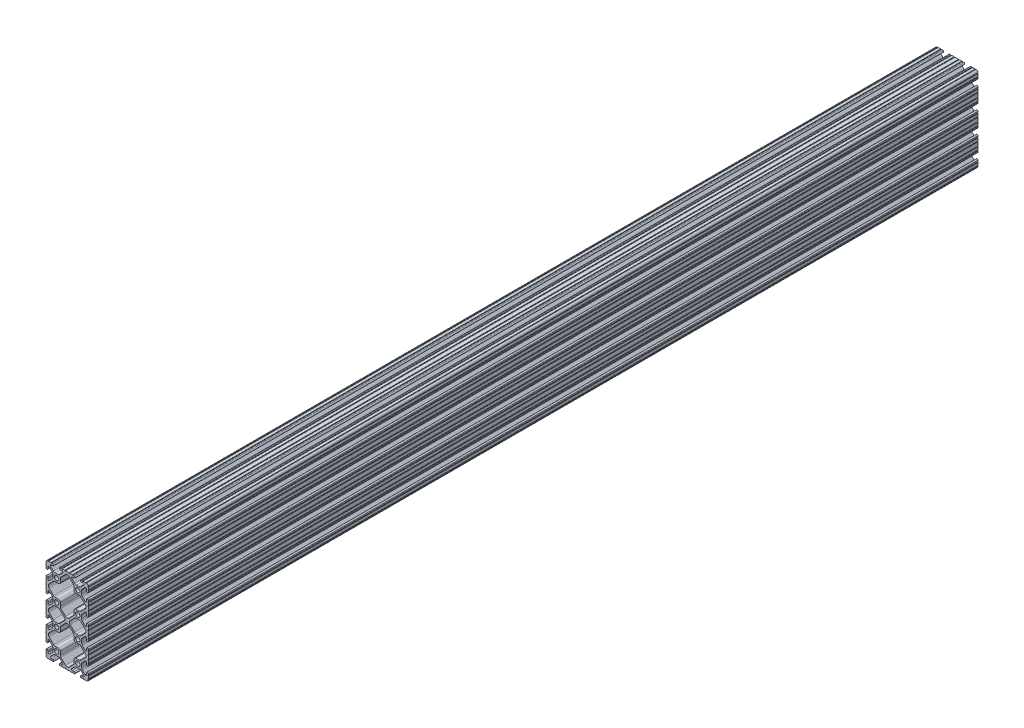
SolidWorks part; units mm, degrees
ref_plane "Front Plane" through (0, 0, 0) normal (0, 0, 1) x (1, 0, 0)
ref_plane "Top Plane" through (0, 0, 0) normal (0, 1, 0) x (1, 0, 0)
ref_plane "Right Plane" through (0, 0, 0) normal (1, 0, 0) x (0, 0, -1)
sketch "Sketch1" plane through (0, 0, 0) normal (0, 0, 1) x (1, 0, 0)
  line L0 (2.286, 55.2958) -> (-2.0184, 55.2958)
  line L1 (-3.5809, 55.943) -> (-9.0725, 61.4345)
  line L2 (-9.0725, 65.5655) -> (-3.5809, 71.057)
  line L3 (-2.0184, 71.7042) -> (2.286, 71.7042)
  line L4 (4.4958, 73.914) -> (4.4958, 78.2184)
  line L5 (5.143, 79.7809) -> (10.6345, 85.2725)
  line L6 (14.7655, 85.2725) -> (20.257, 79.7809)
  line L7 (20.9042, 78.2184) -> (20.9042, 73.914)
  line L8 (23.114, 71.7042) -> (27.4184, 71.7042)
  line L9 (28.9809, 71.057) -> (34.4725, 65.5655)
  line L10 (34.4725, 61.4345) -> (28.9809, 55.943)
  line L11 (27.4184, 55.2958) -> (23.114, 55.2958)
  line L12 (20.9042, 53.086) -> (20.9042, 48.7816)
  line L13 (20.257, 47.2191) -> (14.7655, 41.7275)
  line L14 (10.6345, 41.7275) -> (5.143, 47.2191)
  line L15 (4.4958, 48.7816) -> (4.4958, 53.086)
  line L16 (4.4958, 23.114) -> (4.4958, 27.4184)
  line L17 (5.143, 28.9809) -> (10.6345, 34.4725)
  line L18 (14.7655, 34.4725) -> (20.257, 28.9809)
  line L19 (20.9042, 27.4184) -> (20.9042, 23.114)
  line L20 (23.114, 20.9042) -> (27.4184, 20.9042)
  line L21 (28.9809, 20.257) -> (34.4725, 14.7655)
  line L22 (34.4725, 10.6345) -> (28.9809, 5.143)
  line L23 (27.4184, 4.4958) -> (23.114, 4.4958)
  line L24 (20.9042, 2.286) -> (20.9042, -2.0184)
  line L25 (20.257, -3.5809) -> (14.7655, -9.0725)
  line L26 (10.6345, -9.0725) -> (5.143, -3.5809)
  line L27 (4.4958, -2.0184) -> (4.4958, 2.286)
  line L28 (2.286, 4.4958) -> (-2.0184, 4.4958)
  line L29 (-3.5809, 5.143) -> (-9.0725, 10.6345)
  line L30 (-9.0725, 14.7655) -> (-3.5809, 20.257)
  line L31 (-2.0184, 20.9042) -> (2.286, 20.9042)
  line L32 (27.0186, 29.8958) -> (23.7824, 29.8958)
  line L33 (21.5373, 30.8258) -> (16.3286, 36.0346)
  line L34 (16.3286, 40.1654) -> (21.5373, 45.3742)
  line L35 (23.7824, 46.3042) -> (27.0186, 46.3042)
  line L36 (29.2636, 45.3743) -> (34.4725, 40.1655)
  line L37 (34.4725, 36.0345) -> (29.2636, 30.8257)
  line L38 (1.6176, 29.8958) -> (-1.6186, 29.8958)
  line L39 (-3.8636, 30.8257) -> (-9.0725, 36.0345)
  line L40 (-9.0725, 40.1655) -> (-3.8636, 45.3743)
  line L41 (-1.6186, 46.3042) -> (1.6176, 46.3042)
  line L42 (3.8627, 45.3742) -> (9.0714, 40.1654)
  line L43 (9.0714, 36.0346) -> (3.8627, 30.8258)
  line L44 (-12.7, 40.2336) -> (-12.7, 35.9664)
  line L45 (-12.7, 34.9504) -> (-12.7, 32.004)
  line L46 (-12.7, 30.988) -> (-12.7, 29.7434)
  line L47 (-10.4902, 29.7434) -> (-10.4902, 31.8743)
  line L48 (-8.7558, 32.5927) -> (-5.4258, 29.2627)
  line L49 (-4.4958, 27.0176) -> (-4.4958, 23.7824)
  line L50 (-5.4258, 21.5373) -> (-8.7558, 18.2073)
  line L51 (-10.4902, 18.9257) -> (-10.4902, 21.0566)
  line L52 (-12.7, 21.0566) -> (-12.7, 19.812)
  line L53 (-12.7, 18.796) -> (-12.7, 15.8496)
  line L54 (-12.7, 14.8336) -> (-12.7, 10.5664)
  line L55 (-12.7, 9.5504) -> (-12.7, 6.604)
  line L56 (-12.7, 5.588) -> (-12.7, 4.3434)
  line L57 (-10.4902, 4.3434) -> (-10.4902, 6.4743)
  line L58 (-8.7558, 7.1927) -> (-5.4258, 3.8627)
  line L59 (-4.4958, 1.6176) -> (-4.4958, -1.6176)
  line L60 (-5.4258, -3.8627) -> (-8.7558, -7.1927)
  line L61 (-10.4902, -6.4743) -> (-10.4902, -4.3434)
  line L62 (-12.7, -4.3434) -> (-12.7, -5.588)
  line L63 (-12.7, -6.604) -> (-12.7, -9.5504)
  line L64 (-9.5504, -12.7) -> (-6.604, -12.7)
  line L65 (-5.588, -12.7) -> (-4.3434, -12.7)
  line L66 (-4.3434, -10.4902) -> (-6.4743, -10.4902)
  line L67 (-7.1927, -8.7558) -> (-3.8627, -5.4258)
  line L68 (-1.6176, -4.4958) -> (1.6176, -4.4958)
  line L69 (3.8627, -5.4258) -> (7.1927, -8.7558)
  line L70 (6.4743, -10.4902) -> (4.3434, -10.4902)
  line L71 (4.3434, -12.7) -> (5.588, -12.7)
  line L72 (6.604, -12.7) -> (9.5504, -12.7)
  line L73 (10.5664, -12.7) -> (14.8336, -12.7)
  line L74 (15.8496, -12.7) -> (18.796, -12.7)
  line L75 (19.812, -12.7) -> (21.0566, -12.7)
  line L76 (21.0566, -10.4902) -> (18.9257, -10.4902)
  line L77 (18.2073, -8.7558) -> (21.5373, -5.4258)
  line L78 (23.7824, -4.4958) -> (27.0176, -4.4958)
  line L79 (29.2627, -5.4258) -> (32.5927, -8.7558)
  line L80 (31.8743, -10.4902) -> (29.7434, -10.4902)
  line L81 (29.7434, -12.7) -> (30.988, -12.7)
  line L82 (32.004, -12.7) -> (34.9504, -12.7)
  line L83 (38.1, -9.5504) -> (38.1, -6.604)
  line L84 (38.1, -5.588) -> (38.1, -4.3434)
  line L85 (35.8902, -4.3434) -> (35.8902, -6.4743)
  line L86 (34.1558, -7.1927) -> (30.8258, -3.8627)
  line L87 (29.8958, -1.6176) -> (29.8958, 1.6176)
  line L88 (30.8258, 3.8627) -> (34.1558, 7.1927)
  line L89 (35.8902, 6.4743) -> (35.8902, 4.3434)
  line L90 (38.1, 4.3434) -> (38.1, 5.588)
  line L91 (38.1, 6.604) -> (38.1, 9.5504)
  line L92 (38.1, 10.5664) -> (38.1, 14.8336)
  line L93 (38.1, 15.8496) -> (38.1, 18.796)
  line L94 (38.1, 19.812) -> (38.1, 21.0566)
  line L95 (35.8902, 21.0566) -> (35.8902, 18.9257)
  line L96 (34.1558, 18.2073) -> (30.8258, 21.5373)
  line L97 (29.8958, 23.7824) -> (29.8958, 27.0176)
  line L98 (30.8258, 29.2627) -> (34.1558, 32.5927)
  line L99 (35.8902, 31.8743) -> (35.8902, 29.7434)
  line L100 (38.1, 29.7434) -> (38.1, 30.988)
  line L101 (38.1, 32.004) -> (38.1, 34.9504)
  line L102 (38.1, 35.9664) -> (38.1, 40.2336)
  line L103 (38.1, 41.2496) -> (38.1, 44.196)
  line L104 (38.1, 45.212) -> (38.1, 46.4566)
  line L105 (35.8902, 46.4566) -> (35.8902, 44.3257)
  line L106 (34.1558, 43.6073) -> (30.8258, 46.9373)
  line L107 (29.8958, 49.1824) -> (29.8958, 52.4176)
  line L108 (30.8258, 54.6627) -> (34.1558, 57.9927)
  line L109 (35.8902, 57.2743) -> (35.8902, 55.1434)
  line L110 (38.1, 55.1434) -> (38.1, 56.388)
  line L111 (38.1, 57.404) -> (38.1, 60.3504)
  line L112 (38.1, 61.3664) -> (38.1, 65.6336)
  line L113 (38.1, 66.6496) -> (38.1, 69.596)
  line L114 (38.1, 70.612) -> (38.1, 71.8566)
  line L115 (35.8902, 71.8566) -> (35.8902, 69.7257)
  line L116 (34.1558, 69.0073) -> (30.8258, 72.3373)
  line L117 (29.8958, 74.5824) -> (29.8958, 77.8176)
  line L118 (30.8258, 80.0627) -> (34.1558, 83.3927)
  line L119 (35.8902, 82.6743) -> (35.8902, 80.5434)
  line L120 (38.1, 80.5434) -> (38.1, 81.788)
  line L121 (38.1, 82.804) -> (38.1, 85.7504)
  line L122 (34.9504, 88.9) -> (32.004, 88.9)
  line L123 (30.988, 88.9) -> (29.7434, 88.9)
  line L124 (29.7434, 86.6902) -> (31.8743, 86.6902)
  line L125 (32.5927, 84.9558) -> (29.2627, 81.6258)
  line L126 (27.0176, 80.6958) -> (23.7824, 80.6958)
  line L127 (21.5373, 81.6258) -> (18.2073, 84.9558)
  line L128 (18.9257, 86.6902) -> (21.0566, 86.6902)
  line L129 (21.0566, 88.9) -> (19.812, 88.9)
  line L130 (18.796, 88.9) -> (15.8496, 88.9)
  line L131 (14.8336, 88.9) -> (10.5664, 88.9)
  line L132 (9.5504, 88.9) -> (6.604, 88.9)
  line L133 (5.588, 88.9) -> (4.3434, 88.9)
  line L134 (4.3434, 86.6902) -> (6.4743, 86.6902)
  line L135 (7.1927, 84.9558) -> (3.8627, 81.6258)
  line L136 (1.6176, 80.6958) -> (-1.6176, 80.6958)
  line L137 (-3.8627, 81.6258) -> (-7.1927, 84.9558)
  line L138 (-6.4743, 86.6902) -> (-4.3434, 86.6902)
  line L139 (-4.3434, 88.9) -> (-5.588, 88.9)
  line L140 (-6.604, 88.9) -> (-9.5504, 88.9)
  line L141 (-12.7, 85.7504) -> (-12.7, 82.804)
  line L142 (-12.7, 81.788) -> (-12.7, 80.5434)
  line L143 (-10.4902, 80.5434) -> (-10.4902, 82.6743)
  line L144 (-8.7558, 83.3927) -> (-5.4258, 80.0627)
  line L145 (-4.4958, 77.8176) -> (-4.4958, 74.5824)
  line L146 (-5.4258, 72.3373) -> (-8.7558, 69.0073)
  line L147 (-10.4902, 69.7257) -> (-10.4902, 71.8566)
  line L148 (-12.7, 71.8566) -> (-12.7, 70.612)
  line L149 (-12.7, 69.596) -> (-12.7, 66.6496)
  line L150 (-12.7, 65.6336) -> (-12.7, 61.3664)
  line L151 (-12.7, 60.3504) -> (-12.7, 57.404)
  line L152 (-12.7, 56.388) -> (-12.7, 55.1434)
  line L153 (-10.4902, 55.1434) -> (-10.4902, 57.2743)
  line L154 (-8.7558, 57.9927) -> (-5.4258, 54.6627)
  line L155 (-4.4958, 52.4176) -> (-4.4958, 49.1824)
  line L156 (-5.4258, 46.9373) -> (-8.7558, 43.6073)
  line L157 (-10.4902, 44.3257) -> (-10.4902, 46.4566)
  line L158 (-12.7, 46.4566) -> (-12.7, 45.212)
  line L159 (-12.7, 44.196) -> (-12.7, 41.2496)
  arc A0 (4.4958, 53.086) -> (2.286, 55.2958) centre (2.286, 53.086) ccw
  arc A1 (-3.5809, 55.943) -> (-2.0184, 55.2958) centre (-2.0184, 57.5056) ccw
  arc A2 (-9.0725, 65.5655) -> (-9.0725, 61.4345) centre (-7.0071, 63.5) ccw
  arc A3 (-2.0184, 71.7042) -> (-3.5809, 71.057) centre (-2.0184, 69.4944) ccw
  arc A4 (2.286, 71.7042) -> (4.4958, 73.914) centre (2.286, 73.914) ccw
  arc A5 (5.143, 79.7809) -> (4.4958, 78.2184) centre (6.7056, 78.2184) ccw
  arc A6 (14.7655, 85.2725) -> (10.6345, 85.2725) centre (12.7, 83.2071) ccw
  arc A7 (20.9042, 78.2184) -> (20.257, 79.7809) centre (18.6944, 78.2184) ccw
  arc A8 (20.9042, 73.914) -> (23.114, 71.7042) centre (23.114, 73.914) ccw
  arc A9 (28.9809, 71.057) -> (27.4184, 71.7042) centre (27.4184, 69.4944) ccw
  arc A10 (34.4725, 61.4345) -> (34.4725, 65.5655) centre (32.4071, 63.5) ccw
  arc A11 (27.4184, 55.2958) -> (28.9809, 55.943) centre (27.4184, 57.5056) ccw
  arc A12 (23.114, 55.2958) -> (20.9042, 53.086) centre (23.114, 53.086) ccw
  arc A13 (20.257, 47.2191) -> (20.9042, 48.7816) centre (18.6944, 48.7816) ccw
  arc A14 (10.6345, 41.7275) -> (14.7655, 41.7275) centre (12.7, 43.7929) ccw
  arc A15 (4.4958, 48.7816) -> (5.143, 47.2191) centre (6.7056, 48.7816) ccw
  arc A16 (2.286, 20.9042) -> (4.4958, 23.114) centre (2.286, 23.114) ccw
  arc A17 (5.143, 28.9809) -> (4.4958, 27.4184) centre (6.7056, 27.4184) ccw
  arc A18 (14.7655, 34.4725) -> (10.6345, 34.4725) centre (12.7, 32.4071) ccw
  arc A19 (20.9042, 27.4184) -> (20.257, 28.9809) centre (18.6944, 27.4184) ccw
  arc A20 (20.9042, 23.114) -> (23.114, 20.9042) centre (23.114, 23.114) ccw
  arc A21 (28.9809, 20.257) -> (27.4184, 20.9042) centre (27.4184, 18.6944) ccw
  arc A22 (34.4725, 10.6345) -> (34.4725, 14.7655) centre (32.4071, 12.7) ccw
  arc A23 (27.4184, 4.4958) -> (28.9809, 5.143) centre (27.4184, 6.7056) ccw
  arc A24 (23.114, 4.4958) -> (20.9042, 2.286) centre (23.114, 2.286) ccw
  arc A25 (20.257, -3.5809) -> (20.9042, -2.0184) centre (18.6944, -2.0184) ccw
  arc A26 (10.6345, -9.0725) -> (14.7655, -9.0725) centre (12.7, -7.0071) ccw
  arc A27 (4.4958, -2.0184) -> (5.143, -3.5809) centre (6.7056, -2.0184) ccw
  arc A28 (4.4958, 2.286) -> (2.286, 4.4958) centre (2.286, 2.286) ccw
  arc A29 (-3.5809, 5.143) -> (-2.0184, 4.4958) centre (-2.0184, 6.7056) ccw
  arc A30 (-9.0725, 14.7655) -> (-9.0725, 10.6345) centre (-7.0071, 12.7) ccw
  arc A31 (-2.0184, 20.9042) -> (-3.5809, 20.257) centre (-2.0184, 18.6944) ccw
  arc A32 (27.0186, 29.8958) -> (29.2636, 30.8257) centre (27.0186, 33.0708) ccw
  arc A33 (21.5373, 30.8258) -> (23.7824, 29.8958) centre (23.7824, 33.0708) ccw
  arc A34 (16.3286, 40.1654) -> (16.3286, 36.0346) centre (18.3941, 38.1) ccw
  arc A35 (23.7824, 46.3042) -> (21.5373, 45.3742) centre (23.7824, 43.1292) ccw
  arc A36 (29.2636, 45.3743) -> (27.0186, 46.3042) centre (27.0186, 43.1292) ccw
  arc A37 (34.4725, 36.0345) -> (34.4725, 40.1655) centre (32.4071, 38.1) ccw
  arc A38 (1.6176, 29.8958) -> (3.8627, 30.8258) centre (1.6176, 33.0708) ccw
  arc A39 (-3.8636, 30.8257) -> (-1.6186, 29.8958) centre (-1.6186, 33.0708) ccw
  arc A40 (-9.0725, 40.1655) -> (-9.0725, 36.0345) centre (-7.0071, 38.1) ccw
  arc A41 (-1.6186, 46.3042) -> (-3.8636, 45.3743) centre (-1.6186, 43.1292) ccw
  arc A42 (3.8627, 45.3742) -> (1.6176, 46.3042) centre (1.6176, 43.1292) ccw
  arc A43 (9.0714, 36.0346) -> (9.0714, 40.1654) centre (7.0059, 38.1) ccw
  circle A44 centre (25.4, 76.2) radius 2.6035
  circle A45 centre (0, 76.2) radius 2.6035
  circle A46 centre (25.4, 50.8) radius 2.6035
  circle A47 centre (0, 50.8) radius 2.6035
  circle A48 centre (25.4, 0) radius 2.6035
  circle A49 centre (0, 0) radius 2.6035
  circle A50 centre (25.4, 25.4) radius 2.6035
  circle A51 centre (0, 25.4) radius 2.6035
  arc A52 (-12.7, 34.9504) -> (-12.7, 35.9664) centre (-12.7, 35.4584) ccw
  arc A53 (-12.7, 30.988) -> (-12.7, 32.004) centre (-12.7, 31.496) ccw
  arc A54 (-12.7, 29.7434) -> (-10.4902, 29.7434) centre (-11.5951, 29.7434) ccw
  arc A55 (-8.7558, 32.5927) -> (-10.4902, 31.8743) centre (-9.4742, 31.8743) ccw
  arc A56 (-4.4958, 27.0176) -> (-5.4258, 29.2627) centre (-7.6708, 27.0176) ccw
  arc A57 (-5.4258, 21.5373) -> (-4.4958, 23.7824) centre (-7.6708, 23.7824) ccw
  arc A58 (-10.4902, 18.9257) -> (-8.7558, 18.2073) centre (-9.4742, 18.9257) ccw
  arc A59 (-10.4902, 21.0566) -> (-12.7, 21.0566) centre (-11.5951, 21.0566) ccw
  arc A60 (-12.7, 18.796) -> (-12.7, 19.812) centre (-12.7, 19.304) ccw
  arc A61 (-12.7, 14.8336) -> (-12.7, 15.8496) centre (-12.7, 15.3416) ccw
  arc A62 (-12.7, 9.5504) -> (-12.7, 10.5664) centre (-12.7, 10.0584) ccw
  arc A63 (-12.7, 5.588) -> (-12.7, 6.604) centre (-12.7, 6.096) ccw
  arc A64 (-12.7, 4.3434) -> (-10.4902, 4.3434) centre (-11.5951, 4.3434) ccw
  arc A65 (-8.7558, 7.1927) -> (-10.4902, 6.4743) centre (-9.4742, 6.4743) ccw
  arc A66 (-4.4958, 1.6176) -> (-5.4258, 3.8627) centre (-7.6708, 1.6176) ccw
  arc A67 (-5.4258, -3.8627) -> (-4.4958, -1.6176) centre (-7.6708, -1.6176) ccw
  arc A68 (-10.4902, -6.4743) -> (-8.7558, -7.1927) centre (-9.4742, -6.4743) ccw
  arc A69 (-10.4902, -4.3434) -> (-12.7, -4.3434) centre (-11.5951, -4.3434) ccw
  arc A70 (-12.7, -6.604) -> (-12.7, -5.588) centre (-12.7, -6.096) ccw
  arc A71 (-12.6998, -10.5664) -> (-12.7, -9.5504) centre (-12.7, -10.0584) ccw
  arc A72 (-12.6998, -10.5664) -> (-10.5664, -12.6998) centre (-10.5918, -10.5918) ccw
  arc A73 (-9.5504, -12.7) -> (-10.5664, -12.6998) centre (-10.0584, -12.7) ccw
  arc A74 (-5.588, -12.7) -> (-6.604, -12.7) centre (-6.096, -12.7) ccw
  arc A75 (-4.3434, -12.7) -> (-4.3434, -10.4902) centre (-4.3434, -11.5951) ccw
  arc A76 (-7.1927, -8.7558) -> (-6.4743, -10.4902) centre (-6.4743, -9.4742) ccw
  arc A77 (-1.6176, -4.4958) -> (-3.8627, -5.4258) centre (-1.6176, -7.6708) ccw
  arc A78 (3.8627, -5.4258) -> (1.6176, -4.4958) centre (1.6176, -7.6708) ccw
  arc A79 (6.4743, -10.4902) -> (7.1927, -8.7558) centre (6.4743, -9.4742) ccw
  arc A80 (4.3434, -10.4902) -> (4.3434, -12.7) centre (4.3434, -11.5951) ccw
  arc A81 (6.604, -12.7) -> (5.588, -12.7) centre (6.096, -12.7) ccw
  arc A82 (10.5664, -12.7) -> (9.5504, -12.7) centre (10.0584, -12.7) ccw
  arc A83 (15.8496, -12.7) -> (14.8336, -12.7) centre (15.3416, -12.7) ccw
  arc A84 (19.812, -12.7) -> (18.796, -12.7) centre (19.304, -12.7) ccw
  arc A85 (21.0566, -12.7) -> (21.0566, -10.4902) centre (21.0566, -11.5951) ccw
  arc A86 (18.2073, -8.7558) -> (18.9257, -10.4902) centre (18.9257, -9.4742) ccw
  arc A87 (23.7824, -4.4958) -> (21.5373, -5.4258) centre (23.7824, -7.6708) ccw
  arc A88 (29.2627, -5.4258) -> (27.0176, -4.4958) centre (27.0176, -7.6708) ccw
  arc A89 (31.8743, -10.4902) -> (32.5927, -8.7558) centre (31.8743, -9.4742) ccw
  arc A90 (29.7434, -10.4902) -> (29.7434, -12.7) centre (29.7434, -11.5951) ccw
  arc A91 (32.004, -12.7) -> (30.988, -12.7) centre (31.496, -12.7) ccw
  arc A92 (35.9664, -12.6998) -> (34.9504, -12.7) centre (35.4584, -12.7) ccw
  arc A93 (35.9664, -12.6998) -> (38.0998, -10.5664) centre (35.9918, -10.5918) ccw
  arc A94 (38.1, -9.5504) -> (38.0998, -10.5664) centre (38.1, -10.0584) ccw
  arc A95 (38.1, -5.588) -> (38.1, -6.604) centre (38.1, -6.096) ccw
  arc A96 (38.1, -4.3434) -> (35.8902, -4.3434) centre (36.9951, -4.3434) ccw
  arc A97 (34.1558, -7.1927) -> (35.8902, -6.4743) centre (34.8742, -6.4743) ccw
  arc A98 (29.8958, -1.6176) -> (30.8258, -3.8627) centre (33.0708, -1.6176) ccw
  arc A99 (30.8258, 3.8627) -> (29.8958, 1.6176) centre (33.0708, 1.6176) ccw
  arc A100 (35.8902, 6.4743) -> (34.1558, 7.1927) centre (34.8742, 6.4743) ccw
  arc A101 (35.8902, 4.3434) -> (38.1, 4.3434) centre (36.9951, 4.3434) ccw
  arc A102 (38.1, 6.604) -> (38.1, 5.588) centre (38.1, 6.096) ccw
  arc A103 (38.1, 10.5664) -> (38.1, 9.5504) centre (38.1, 10.0584) ccw
  arc A104 (38.1, 15.8496) -> (38.1, 14.8336) centre (38.1, 15.3416) ccw
  arc A105 (38.1, 19.812) -> (38.1, 18.796) centre (38.1, 19.304) ccw
  arc A106 (38.1, 21.0566) -> (35.8902, 21.0566) centre (36.9951, 21.0566) ccw
  arc A107 (34.1558, 18.2073) -> (35.8902, 18.9257) centre (34.8742, 18.9257) ccw
  arc A108 (29.8958, 23.7824) -> (30.8258, 21.5373) centre (33.0708, 23.7824) ccw
  arc A109 (30.8258, 29.2627) -> (29.8958, 27.0176) centre (33.0708, 27.0176) ccw
  arc A110 (35.8902, 31.8743) -> (34.1558, 32.5927) centre (34.8742, 31.8743) ccw
  arc A111 (35.8902, 29.7434) -> (38.1, 29.7434) centre (36.9951, 29.7434) ccw
  arc A112 (38.1, 32.004) -> (38.1, 30.988) centre (38.1, 31.496) ccw
  arc A113 (38.1, 35.9664) -> (38.1, 34.9504) centre (38.1, 35.4584) ccw
  arc A114 (38.1, 41.2496) -> (38.1, 40.2336) centre (38.1, 40.7416) ccw
  arc A115 (38.1, 45.212) -> (38.1, 44.196) centre (38.1, 44.704) ccw
  arc A116 (38.1, 46.4566) -> (35.8902, 46.4566) centre (36.9951, 46.4566) ccw
  arc A117 (34.1558, 43.6073) -> (35.8902, 44.3257) centre (34.8742, 44.3257) ccw
  arc A118 (29.8958, 49.1824) -> (30.8258, 46.9373) centre (33.0708, 49.1824) ccw
  arc A119 (30.8258, 54.6627) -> (29.8958, 52.4176) centre (33.0708, 52.4176) ccw
  arc A120 (35.8902, 57.2743) -> (34.1558, 57.9927) centre (34.8742, 57.2743) ccw
  arc A121 (35.8902, 55.1434) -> (38.1, 55.1434) centre (36.9951, 55.1434) ccw
  arc A122 (38.1, 57.404) -> (38.1, 56.388) centre (38.1, 56.896) ccw
  arc A123 (38.1, 61.3664) -> (38.1, 60.3504) centre (38.1, 60.8584) ccw
  arc A124 (38.1, 66.6496) -> (38.1, 65.6336) centre (38.1, 66.1416) ccw
  arc A125 (38.1, 70.612) -> (38.1, 69.596) centre (38.1, 70.104) ccw
  arc A126 (38.1, 71.8566) -> (35.8902, 71.8566) centre (36.9951, 71.8566) ccw
  arc A127 (34.1558, 69.0073) -> (35.8902, 69.7257) centre (34.8742, 69.7257) ccw
  arc A128 (29.8958, 74.5824) -> (30.8258, 72.3373) centre (33.0708, 74.5824) ccw
  arc A129 (30.8258, 80.0627) -> (29.8958, 77.8176) centre (33.0708, 77.8176) ccw
  arc A130 (35.8902, 82.6743) -> (34.1558, 83.3927) centre (34.8742, 82.6743) ccw
  arc A131 (35.8902, 80.5434) -> (38.1, 80.5434) centre (36.9951, 80.5434) ccw
  arc A132 (38.1, 82.804) -> (38.1, 81.788) centre (38.1, 82.296) ccw
  arc A133 (38.0998, 86.7664) -> (38.1, 85.7504) centre (38.1, 86.2584) ccw
  arc A134 (38.0998, 86.7664) -> (35.9664, 88.8998) centre (35.9918, 86.7918) ccw
  arc A135 (34.9504, 88.9) -> (35.9664, 88.8998) centre (35.4584, 88.9) ccw
  arc A136 (30.988, 88.9) -> (32.004, 88.9) centre (31.496, 88.9) ccw
  arc A137 (29.7434, 88.9) -> (29.7434, 86.6902) centre (29.7434, 87.7951) ccw
  arc A138 (32.5927, 84.9558) -> (31.8743, 86.6902) centre (31.8743, 85.6742) ccw
  arc A139 (27.0176, 80.6958) -> (29.2627, 81.6258) centre (27.0176, 83.8708) ccw
  arc A140 (21.5373, 81.6258) -> (23.7824, 80.6958) centre (23.7824, 83.8708) ccw
  arc A141 (18.9257, 86.6902) -> (18.2073, 84.9558) centre (18.9257, 85.6742) ccw
  arc A142 (21.0566, 86.6902) -> (21.0566, 88.9) centre (21.0566, 87.7951) ccw
  arc A143 (18.796, 88.9) -> (19.812, 88.9) centre (19.304, 88.9) ccw
  arc A144 (14.8336, 88.9) -> (15.8496, 88.9) centre (15.3416, 88.9) ccw
  arc A145 (9.5504, 88.9) -> (10.5664, 88.9) centre (10.0584, 88.9) ccw
  arc A146 (5.588, 88.9) -> (6.604, 88.9) centre (6.096, 88.9) ccw
  arc A147 (4.3434, 88.9) -> (4.3434, 86.6902) centre (4.3434, 87.7951) ccw
  arc A148 (7.1927, 84.9558) -> (6.4743, 86.6902) centre (6.4743, 85.6742) ccw
  arc A149 (1.6176, 80.6958) -> (3.8627, 81.6258) centre (1.6176, 83.8708) ccw
  arc A150 (-3.8627, 81.6258) -> (-1.6176, 80.6958) centre (-1.6176, 83.8708) ccw
  arc A151 (-6.4743, 86.6902) -> (-7.1927, 84.9558) centre (-6.4743, 85.6742) ccw
  arc A152 (-4.3434, 86.6902) -> (-4.3434, 88.9) centre (-4.3434, 87.7951) ccw
  arc A153 (-6.604, 88.9) -> (-5.588, 88.9) centre (-6.096, 88.9) ccw
  arc A154 (-10.5664, 88.8998) -> (-9.5504, 88.9) centre (-10.0584, 88.9) ccw
  arc A155 (-10.5664, 88.8998) -> (-12.6998, 86.7664) centre (-10.5918, 86.7918) ccw
  arc A156 (-12.7, 85.7504) -> (-12.6998, 86.7664) centre (-12.7, 86.2584) ccw
  arc A157 (-12.7, 81.788) -> (-12.7, 82.804) centre (-12.7, 82.296) ccw
  arc A158 (-12.7, 80.5434) -> (-10.4902, 80.5434) centre (-11.5951, 80.5434) ccw
  arc A159 (-8.7558, 83.3927) -> (-10.4902, 82.6743) centre (-9.4742, 82.6743) ccw
  arc A160 (-4.4958, 77.8176) -> (-5.4258, 80.0627) centre (-7.6708, 77.8176) ccw
  arc A161 (-5.4258, 72.3373) -> (-4.4958, 74.5824) centre (-7.6708, 74.5824) ccw
  arc A162 (-10.4902, 69.7257) -> (-8.7558, 69.0073) centre (-9.4742, 69.7257) ccw
  arc A163 (-10.4902, 71.8566) -> (-12.7, 71.8566) centre (-11.5951, 71.8566) ccw
  arc A164 (-12.7, 69.596) -> (-12.7, 70.612) centre (-12.7, 70.104) ccw
  arc A165 (-12.7, 65.6336) -> (-12.7, 66.6496) centre (-12.7, 66.1416) ccw
  arc A166 (-12.7, 60.3504) -> (-12.7, 61.3664) centre (-12.7, 60.8584) ccw
  arc A167 (-12.7, 56.388) -> (-12.7, 57.404) centre (-12.7, 56.896) ccw
  arc A168 (-12.7, 55.1434) -> (-10.4902, 55.1434) centre (-11.5951, 55.1434) ccw
  arc A169 (-8.7558, 57.9927) -> (-10.4902, 57.2743) centre (-9.4742, 57.2743) ccw
  arc A170 (-4.4958, 52.4176) -> (-5.4258, 54.6627) centre (-7.6708, 52.4176) ccw
  arc A171 (-5.4258, 46.9373) -> (-4.4958, 49.1824) centre (-7.6708, 49.1824) ccw
  arc A172 (-10.4902, 44.3257) -> (-8.7558, 43.6073) centre (-9.4742, 44.3257) ccw
  arc A173 (-10.4902, 46.4566) -> (-12.7, 46.4566) centre (-11.5951, 46.4566) ccw
  arc A174 (-12.7, 44.196) -> (-12.7, 45.212) centre (-12.7, 44.704) ccw
  arc A175 (-12.7, 40.2336) -> (-12.7, 41.2496) centre (-12.7, 40.7416) ccw
extrude "Extrude1" add sketch "Sketch1" against normal blind 1066.8
